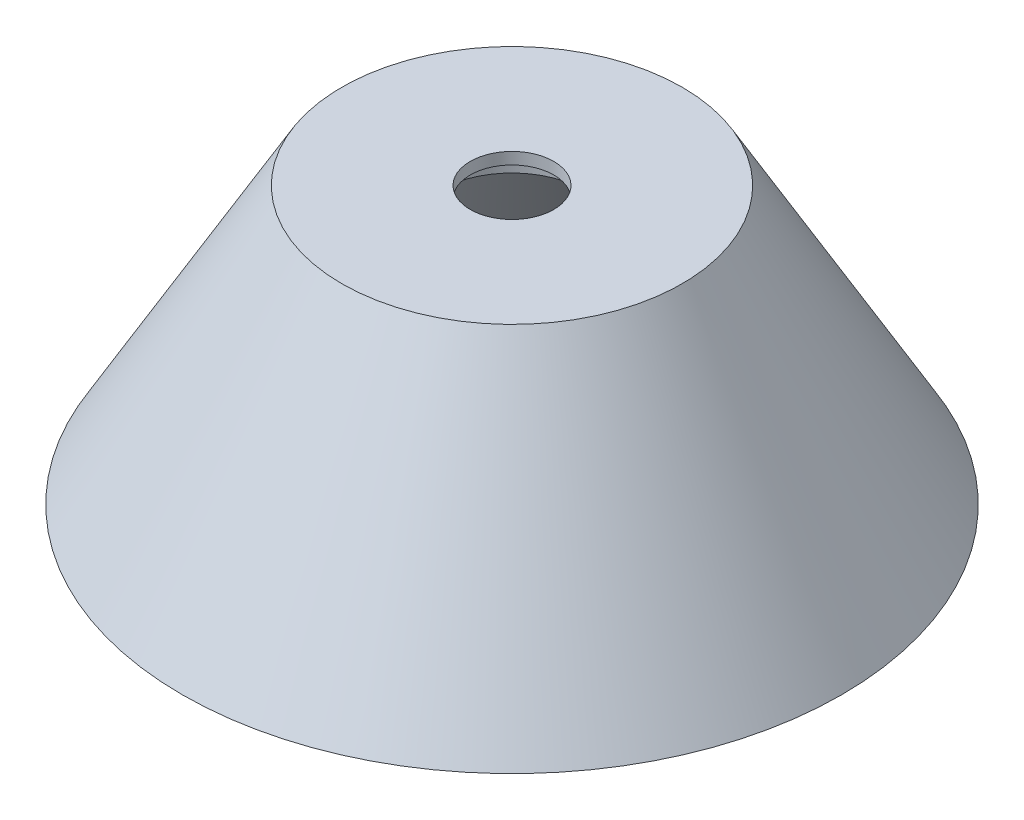
SolidWorks part; units mm, degrees
ref_plane "前视基准面" through (0, 0, 0) normal (0, 0, 1) x (1, 0, 0)
ref_plane "上视基准面" through (0, 0, 0) normal (0, 1, 0) x (1, 0, 0)
ref_plane "右视基准面" through (0, 0, 0) normal (1, 0, 0) x (0, 0, -1)
other "Configuration Table"
sketch "草图2" plane through (0, 0, 0) normal (0, 0, 1) x (1, 0, 0)
  line L0 (0, 0) -> (0, 23.4079) construction
  line L1 (0, 0) -> (-30, 0)
  line L2 (-30, 0) -> (-53.094, -40)
  line L3 (-53.094, -40) -> (-56.094, -40)
  line L4 (-56.094, -40) -> (-28.9585, 7)
  line L5 (-28.9585, 7) -> (0, 7)
  line L6 (0, 0) -> (0, 7)
  dimension "D1" = 60
  dimension "D2" = 120
  dimension "D3" = 40
  dimension "D4" = 7
  dimension "D5" = 3
revolve "旋转1" add sketch "草图2" angle 360 about L0
sketch "草图4" plane through (0, 0, 0) normal (0, -1, 0) x (1, 0, 0)
  circle A0 centre (0, 0) radius 12.5
  dimension "D1" = 25
extrude "切除-拉伸1" cut sketch "草图4" against normal blind 5
sketch "草图5" plane through (0, 5, 0) normal (0, -1, 0) x (1, 0, 0)
  circle A0 centre (0, 0) radius 7.1
  dimension "D1" = 14.2
extrude "切除-拉伸2" cut sketch "草图5" against normal through all
